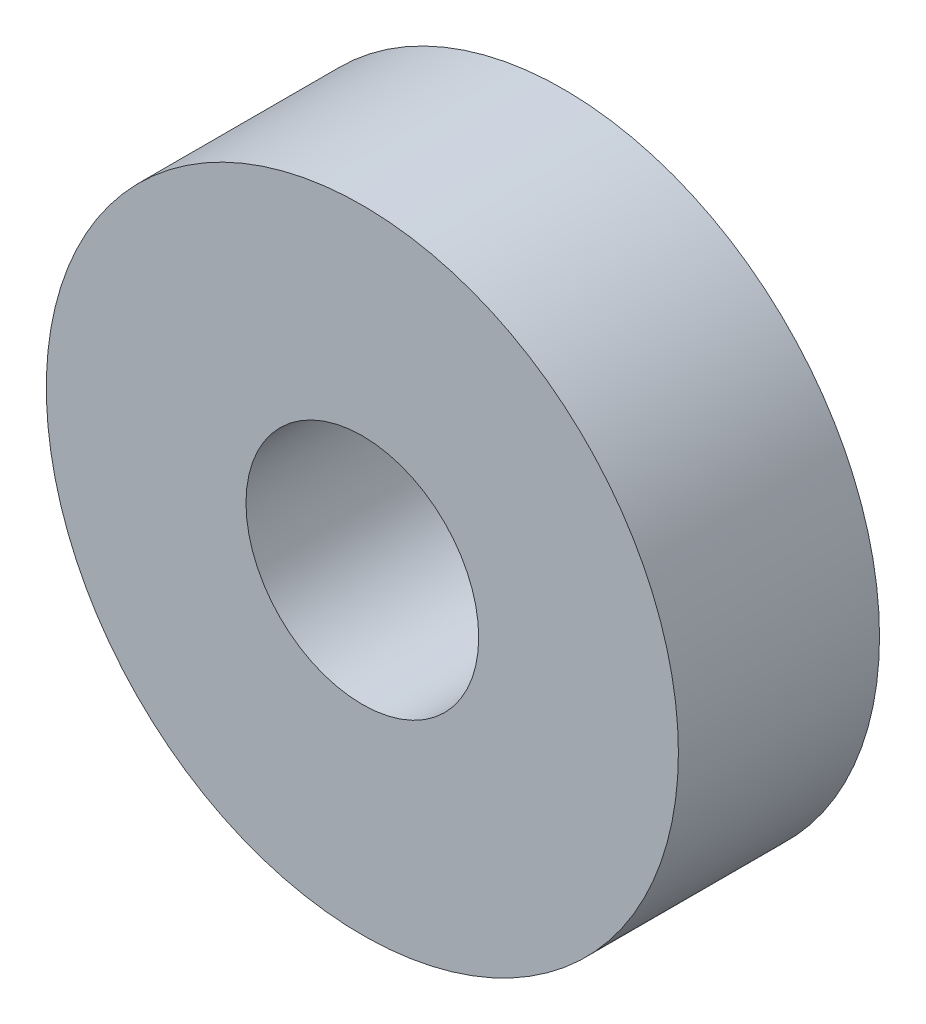
SolidWorks part; units mm, degrees
ref_plane "Front Plane" through (0, 0, 0) normal (0, 0, 1) x (1, 0, 0)
ref_plane "Top Plane" through (0, 0, 0) normal (0, 1, 0) x (1, 0, 0)
ref_plane "Right Plane" through (0, 0, 0) normal (1, 0, 0) x (0, 0, -1)
sketch "Sketch1" plane through (0, 0, 0) normal (0, 0, 1) x (1, 0, 0)
  circle A0 centre (0, 0) radius 4.05
  circle A1 centre (0, 0) radius 11
  dimension "D1" = 22
  dimension "D2" = 8.1
extrude "Boss-Extrude1" add sketch "Sketch1" along normal blind 7
